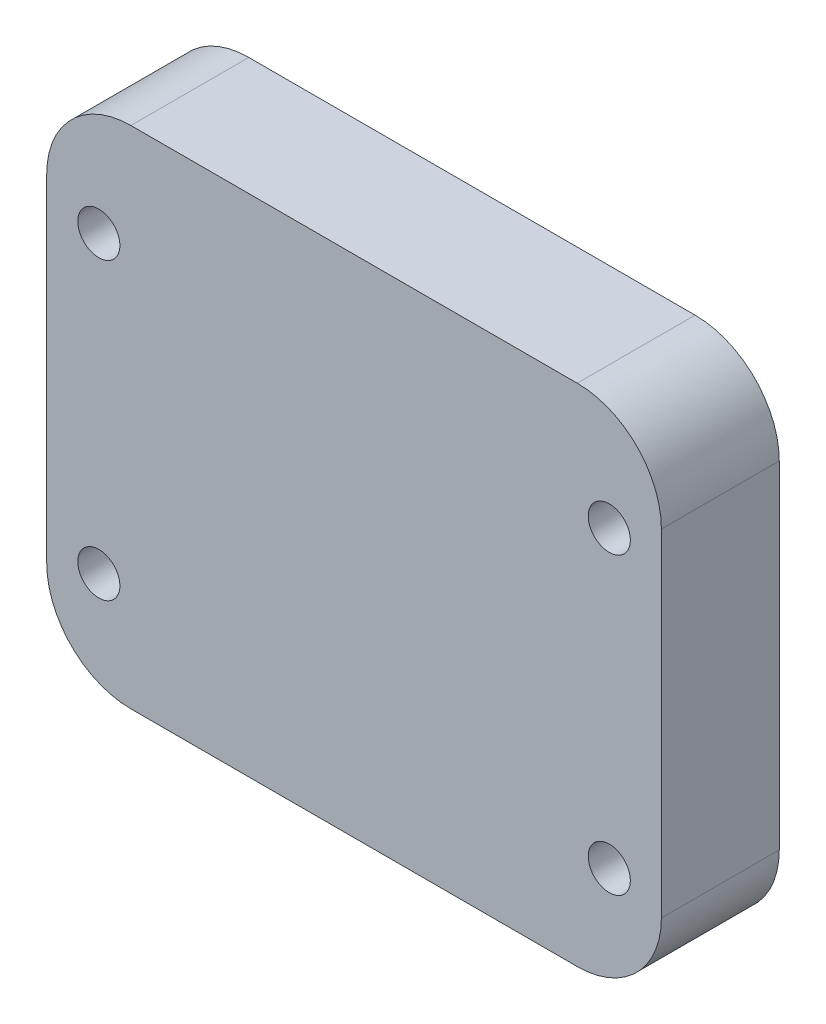
SolidWorks part; units mm, degrees
ref_plane "Ebene vorne" through (0, 0, 0) normal (0, 0, 1) x (1, 0, 0)
ref_plane "Ebene oben" through (0, 0, 0) normal (0, 1, 0) x (1, 0, 0)
ref_plane "Ebene rechts" through (0, 0, 0) normal (1, 0, 0) x (0, 0, -1)
sketch "Sketch1" plane through (0, 0, 0) normal (0, 0, 1) x (1, 0, 0)
  line L1 (36.5, -30) -> (-36.5, -30)
  line L2 (36.5, -30) -> (36.5, 30)
  line L3 (36.5, 30) -> (-36.5, 30)
  line L4 (-36.5, -30) -> (-36.5, 30)
  line L5 (36.5, -30) -> (-36.5, 30) construction
  line L6 (36.5, 30) -> (-36.5, -30) construction
  point P0 (0, 0)
  dimension "D1" = 60
  dimension "D2" = 73
extrude "Plate" add sketch "Sketch1" along normal blind 14
sketch "Sketch2" plane through (0, 0, 14) normal (0, 0, 1) x (1, 0, 0)
  line L0 (-36.5, -30) -> (36.5, -30) construction
  line L1 (-30.3109, 17) -> (30.3109, 17) construction
  line L2 (0, 17) -> (0, 9.0987) construction
  circle A0 centre (-30.3109, 17) radius 2.5
  circle A1 centre (30.3109, 17) radius 2.5
  circle A2 centre (30.3109, -18) radius 2.5
  circle A3 centre (-30.3109, -18) radius 2.5
  dimension "D1" = 5
  dimension "D2" = 12
  dimension "D3" = 35
  dimension "D4" = 60.6218
extrude "Cut-Extrude4" cut sketch "Sketch2" against normal blind 16
fillet "Fillet1" radius 10 1 edges at (36.5, -30, 7)
fillet "Fillet2" radius 10 1 edges at (36.5, 30, 7)
fillet "Fillet3" radius 10 1 edges at (-36.5, 30, 7)
fillet "Fillet4" radius 10 1 edges at (-36.5, -30, 7)
sketch "Sketch3" [suppressed] plane through (0, 0, 0) normal (0, 0, -1) x (-1, 0, 0)
  circle A0 centre (0, 0) radius 45
  dimension "D1" = 90
